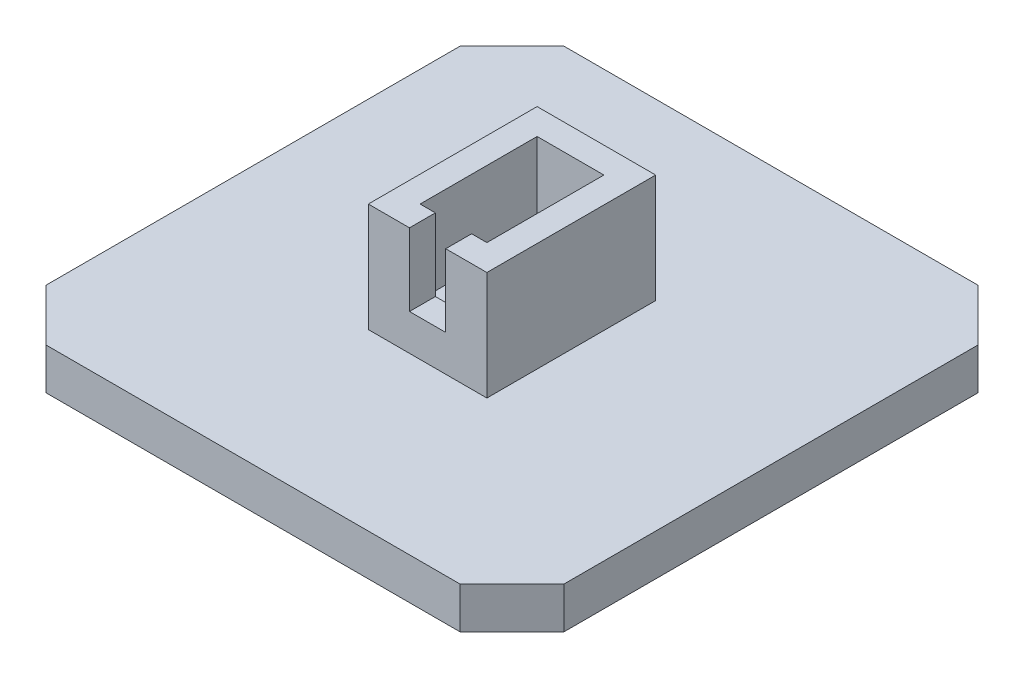
SolidWorks part; units mm, degrees
material "ABS"
ref_plane "Front Plane" through (0, 0, 0) normal (0, 0, 1) x (1, 0, 0)
ref_plane "Top Plane" through (0, 0, 0) normal (0, 1, 0) x (1, 0, 0)
ref_plane "Right Plane" through (0, 0, 0) normal (1, 0, 0) x (0, 0, -1)
sketch "Sketch1" plane through (0, 0, 0) normal (1, 0, 0) x (0, 0, -1)
  line L1 (-11.3, -8) -> (11.3, -8)
  line L2 (-11.3, -8) -> (-11.3, 8)
  line L3 (-11.3, 8) -> (11.3, 8)
  line L4 (11.3, -8) -> (11.3, 8)
  line L5 (-11.3, -8) -> (11.3, 8) construction
  line L6 (-11.3, 8) -> (11.3, -8) construction
  point P0 (0, 0)
  dimension "D1" = 22.6
  dimension "D2" = 16
extrude "base block" add sketch "Sketch1" along normal mid plane 12.9
shell "Shell1" thickness 5
sketch "Sketch2" plane through (0, 0, 0) normal (0, 0, 1) x (1, 0, 0)
  line L0 (6.45, -8) -> (-6.45, -8) construction
  line L1 (6.45, -8) -> (-6.45, -8) construction
  line L2 (0, 0) -> (0, -8) construction
  line L3 (11.45, 8) -> (-11.45, 8) construction
  line L8 (-3.5, -6) -> (3.5, -6)
  line L9 (-3.5, -6) -> (-3.5, 8)
  line L10 (-3.5, 8) -> (3.5, 8)
  line L11 (3.5, -6) -> (3.5, 8)
  point P11 (0, -6)
  dimension "D1" = 7
  dimension "D2" = 2
extrude "cable passthrough" cut sketch "Sketch2" along normal up to next
sketch "Sketch3" plane through (0, -13, 0) normal (0, -1, 0) x (1, 0, 0)
  line L1 (-50, -50) -> (50, -50)
  line L2 (-50, -50) -> (-50, 50)
  line L3 (-50, 50) -> (50, 50)
  line L4 (50, -50) -> (50, 50)
  line L5 (-50, -50) -> (50, 50) construction
  line L6 (-50, 50) -> (50, -50) construction
  point P0 (0, 0)
  dimension "D1" = 100
extrude "base plate" add sketch "Sketch3" along normal blind 8
chamfer "corner chamfer" distance 10 angle 45 4 edges at (50, -17, -50) (-50, -17, -50) (-50, -17, 50) (50, -17, 50)
